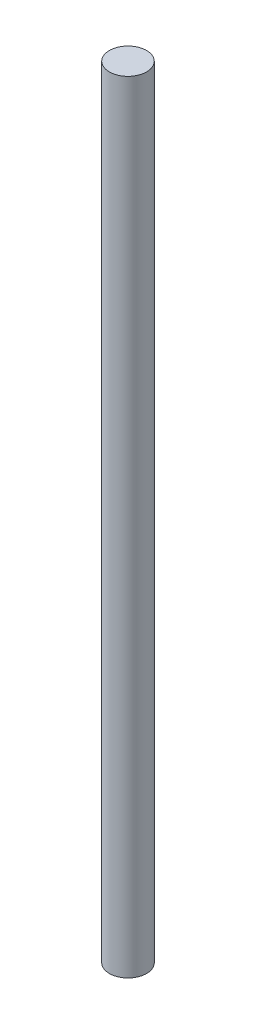
SolidWorks part; units mm, degrees
material "Plain Carbon Steel"
ref_plane "Front Plane" through (0, 0, 0) normal (0, 0, 1) x (1, 0, 0)
ref_plane "Top Plane" through (0, 0, 0) normal (0, 1, 0) x (1, 0, 0)
ref_plane "Right Plane" through (0, 0, 0) normal (1, 0, 0) x (0, 0, -1)
sketch "Sketch1" plane through (0, 0, 0) normal (0, 1, 0) x (1, 0, 0)
  circle A0 centre (0, 0) radius 4.7625
  dimension "D1" = 9.525
extrude "Boss-Extrude1" add sketch "Sketch1" along normal blind 200
